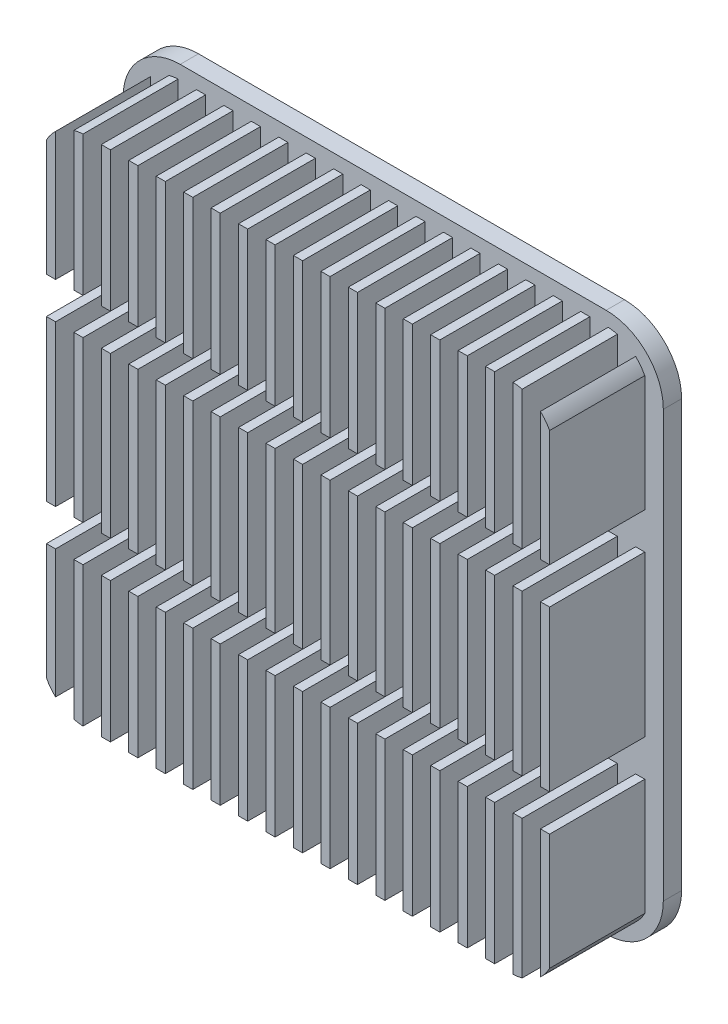
SolidWorks part; units mm, degrees
material "6061 Alloy"
ref_plane "Front Plane" through (0, 0, 0) normal (0, 0, 1) x (1, 0, 0)
ref_plane "Top Plane" through (0, 0, 0) normal (0, 1, 0) x (1, 0, 0)
ref_plane "Right Plane" through (0, 0, 0) normal (1, 0, 0) x (0, 0, -1)
sketch "Sketch1" plane through (0, 0, 0) normal (0, 0, 1) x (1, 0, 0)
  line L1 (-15, 15) -> (15, 15)
  line L2 (-15, 15) -> (-15, -15)
  line L3 (-15, -15) -> (15, -15)
  line L4 (15, 15) -> (15, -15)
  line L5 (-15, 15) -> (15, -15) construction
  line L6 (-15, -15) -> (15, 15) construction
  point P0 (0, 0)
  dimension "D1" = 30
ref_plane "Plane1" through (0, 0, 6.3) normal (0, 0, 1) x (1, 0, 0)
sketch "Sketch2" plane through (0, 0, 0) normal (0, 0, 1) x (1, 0, 0)
  line L0 (-15, 15) -> (-15, -15) construction
  line L1 (-15, -15) -> (15, -15) construction
  line L2 (15, 15) -> (15, -15) construction
  line L3 (-15, 15) -> (15, 15) construction
  line L4 (-15, 11.825) -> (-15, -11.825)
  line L5 (-11.825, -15) -> (11.825, -15)
  line L6 (15, 11.825) -> (15, -11.825)
  line L7 (-11.825, 15) -> (11.825, 15)
  arc A0 (-15, -11.825) -> (-11.825, -15) centre (-11.825, -11.825) ccw
  arc A1 (11.825, -15) -> (15, -11.825) centre (11.825, -11.825) ccw
  arc A2 (15, 11.825) -> (11.825, 15) centre (11.825, 11.825) ccw
  arc A3 (-15, 11.825) -> (-11.825, 15) centre (-11.825, 11.825) cw
  dimension "D1" = 3.175
extrude "Boss-Extrude1" add sketch "Sketch2" along normal blind 1.016
sketch "Sketch3" plane through (0, 0, 1.016) normal (0, 0, 1) x (1, 0, 0)
  line L0 (-15, 15) -> (15, -15) construction
  line L1 (-0.254, 14.5) -> (0.254, 14.5)
  line L2 (-0.254, 14.5) -> (-0.254, -14.5)
  line L3 (-0.254, -14.5) -> (0.254, -14.5)
  line L4 (0.254, 14.5) -> (0.254, -14.5)
  line L5 (-0.254, 14.5) -> (0.254, -14.5) construction
  line L6 (-0.254, -14.5) -> (0.254, 14.5) construction
  line L7 (1.27, 14.5) -> (1.778, 14.5)
  line L8 (1.27, -14.5) -> (1.778, -14.5)
  line L9 (1.27, 14.5) -> (1.27, -14.5)
  line L10 (1.778, 14.5) -> (1.778, -14.5)
  line L11 (2.794, 14.5) -> (3.302, 14.5)
  line L12 (2.794, -14.5) -> (3.302, -14.5)
  line L13 (2.794, 14.5) -> (2.794, -14.5)
  line L14 (3.302, 14.5) -> (3.302, -14.5)
  line L15 (4.318, 14.5) -> (4.826, 14.5)
  line L16 (4.318, -14.5) -> (4.826, -14.5)
  line L17 (4.318, 14.5) -> (4.318, -14.5)
  line L18 (4.826, 14.5) -> (4.826, -14.5)
  line L19 (5.842, 14.5) -> (6.35, 14.5)
  line L20 (5.842, -14.5) -> (6.35, -14.5)
  line L21 (5.842, 14.5) -> (5.842, -14.5)
  line L22 (6.35, 14.5) -> (6.35, -14.5)
  line L23 (7.366, 14.5) -> (7.874, 14.5)
  line L24 (7.366, -14.5) -> (7.874, -14.5)
  line L25 (7.366, 14.5) -> (7.366, -14.5)
  line L26 (7.874, 14.5) -> (7.874, -14.5)
  line L27 (8.89, 14.5) -> (9.398, 14.5)
  line L28 (8.89, -14.5) -> (9.398, -14.5)
  line L29 (8.89, 14.5) -> (8.89, -14.5)
  line L30 (9.398, 14.5) -> (9.398, -14.5)
  line L31 (10.414, 14.5) -> (10.922, 14.5)
  line L32 (10.414, -14.5) -> (10.922, -14.5)
  line L33 (10.414, 14.5) -> (10.414, -14.5)
  line L34 (10.922, 14.5) -> (10.922, -14.5)
  line L35 (11.938, 14.5) -> (12.446, 14.5)
  line L36 (11.938, -14.5) -> (12.446, -14.5)
  line L37 (11.938, 14.5) -> (11.938, -14.5)
  line L38 (12.446, 14.5) -> (12.446, -14.5)
  line L39 (13.462, 14.5) -> (13.97, 14.5)
  line L40 (13.462, -14.5) -> (13.97, -14.5)
  line L41 (13.462, 14.5) -> (13.462, -14.5)
  line L42 (13.97, 14.5) -> (13.97, -14.5)
  line L43 (-1.778, 14.5) -> (-1.27, 14.5)
  line L44 (-1.778, -14.5) -> (-1.27, -14.5)
  line L45 (-1.778, 14.5) -> (-1.778, -14.5)
  line L46 (-1.27, 14.5) -> (-1.27, -14.5)
  line L47 (-3.302, 14.5) -> (-2.794, 14.5)
  line L48 (-3.302, -14.5) -> (-2.794, -14.5)
  line L49 (-3.302, 14.5) -> (-3.302, -14.5)
  line L50 (-2.794, 14.5) -> (-2.794, -14.5)
  line L51 (-4.826, 14.5) -> (-4.318, 14.5)
  line L52 (-4.826, -14.5) -> (-4.318, -14.5)
  line L53 (-4.826, 14.5) -> (-4.826, -14.5)
  line L54 (-4.318, 14.5) -> (-4.318, -14.5)
  line L55 (-6.35, 14.5) -> (-5.842, 14.5)
  line L56 (-6.35, -14.5) -> (-5.842, -14.5)
  line L57 (-6.35, 14.5) -> (-6.35, -14.5)
  line L58 (-5.842, 14.5) -> (-5.842, -14.5)
  line L59 (-7.874, 14.5) -> (-7.366, 14.5)
  line L60 (-7.874, -14.5) -> (-7.366, -14.5)
  line L61 (-7.874, 14.5) -> (-7.874, -14.5)
  line L62 (-7.366, 14.5) -> (-7.366, -14.5)
  line L63 (-9.398, 14.5) -> (-8.89, 14.5)
  line L64 (-9.398, -14.5) -> (-8.89, -14.5)
  line L65 (-9.398, 14.5) -> (-9.398, -14.5)
  line L66 (-8.89, 14.5) -> (-8.89, -14.5)
  line L67 (-10.922, 14.5) -> (-10.414, 14.5)
  line L68 (-10.922, -14.5) -> (-10.414, -14.5)
  line L69 (-10.922, 14.5) -> (-10.922, -14.5)
  line L70 (-10.414, 14.5) -> (-10.414, -14.5)
  line L71 (-12.446, 14.5) -> (-11.938, 14.5)
  line L72 (-12.446, -14.5) -> (-11.938, -14.5)
  line L73 (-12.446, 14.5) -> (-12.446, -14.5)
  line L74 (-11.938, 14.5) -> (-11.938, -14.5)
  line L75 (-13.97, 14.5) -> (-13.462, 14.5)
  line L76 (-13.97, -14.5) -> (-13.462, -14.5)
  line L77 (-13.97, 14.5) -> (-13.97, -14.5)
  line L78 (-13.462, 14.5) -> (-13.462, -14.5)
  point P0 (0, 0)
  dimension "D1" = 29
  dimension "D2" = 0.508
  dimension "D3" = 10
  dimension "D4" = 10
extrude "Boss-Extrude2" add sketch "Sketch3" along normal up to surface (5.284 mm away) up to plane "Plane1"
sketch "Sketch5" plane through (0, 0, 6.3) normal (0, 0, 1) x (1, 0, 0)
  line L0 (-14.238, 11.825) -> (-14.238, -11.825)
  line L1 (-11.825, -14.238) -> (11.825, -14.238)
  line L2 (14.238, -11.825) -> (14.238, 11.825)
  line L3 (11.825, 14.238) -> (-11.825, 14.238)
  line L4 (-15, 11.825) -> (-15, -11.825)
  line L5 (11.825, 15) -> (-11.825, 15)
  line L6 (15, -11.825) -> (15, 11.825)
  line L7 (-11.825, -15) -> (11.825, -15)
  line L8 (-15, 11.825) -> (-15, -11.825) construction
  line L9 (11.825, 15) -> (-11.825, 15) construction
  line L10 (15, -11.825) -> (15, 11.825) construction
  line L11 (-11.825, -15) -> (11.825, -15) construction
  arc A0 (-14.238, -11.825) -> (-11.825, -14.238) centre (-11.825, -11.825) ccw
  arc A1 (11.825, -14.238) -> (14.238, -11.825) centre (11.825, -11.825) ccw
  arc A2 (14.238, 11.825) -> (11.825, 14.238) centre (11.825, 11.825) ccw
  arc A3 (-11.825, 14.238) -> (-14.238, 11.825) centre (-11.825, 11.825) ccw
  arc A4 (-15, -11.825) -> (-11.825, -15) centre (-11.825, -11.825) ccw
  arc A5 (-11.825, 15) -> (-15, 11.825) centre (-11.825, 11.825) ccw
  arc A6 (15, 11.825) -> (11.825, 15) centre (11.825, 11.825) ccw
  arc A7 (11.825, -15) -> (15, -11.825) centre (11.825, -11.825) ccw
  arc A8 (-15, -11.825) -> (-11.825, -15) centre (-11.825, -11.825) ccw construction
  arc A9 (-11.825, 15) -> (-15, 11.825) centre (-11.825, 11.825) ccw construction
  arc A10 (15, 11.825) -> (11.825, 15) centre (11.825, 11.825) ccw construction
  arc A11 (11.825, -15) -> (15, -11.825) centre (11.825, -11.825) ccw construction
  dimension "D1" = 0
  dimension "D2" = 0.762
extrude "Cut-Extrude1" cut sketch "Sketch5" against normal up to surface (5.284 mm away) flip side to cut up to face at (-12.192, 0, 1.016)
sketch "Sketch8" plane through (0, 0, 6.3) normal (0, 0, 1) x (1, 0, 0)
  line L0 (0, 0) -> (-20.2261, 0) construction
  line L1 (15.895, -4.445) -> (15.895, -6.477)
  line L2 (-16.3535, 4.445) -> (15.895, 4.445)
  line L3 (-16.3535, 4.445) -> (-16.3535, 6.477)
  line L4 (-16.3535, 6.477) -> (15.895, 6.477)
  line L5 (15.895, 4.445) -> (15.895, 6.477)
  line L6 (-16.3535, -4.445) -> (-16.3535, -6.477)
  line L7 (-16.3535, -4.445) -> (15.895, -4.445)
  line L8 (-16.3535, -6.477) -> (15.895, -6.477)
  dimension "D1" = 2.032
  dimension "D2" = 8.89
extrude "Cut-Extrude2" cut sketch "Sketch8" against normal up to surface (5.284 mm away) up to face at (-13.7306, 0, 1.016)
